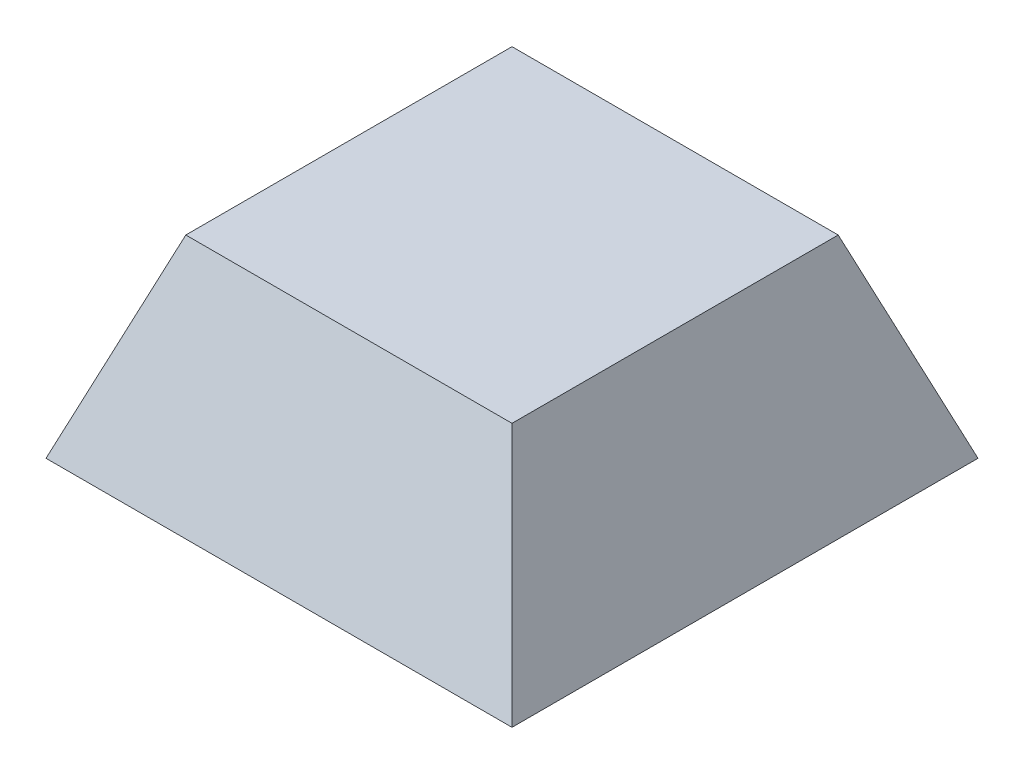
SolidWorks part; units mm, degrees
ref_plane "前视基准面" through (0, 0, 0) normal (0, 0, 1) x (1, 0, 0)
ref_plane "上视基准面" through (0, 0, 0) normal (0, 1, 0) x (1, 0, 0)
ref_plane "右视基准面" through (0, 0, 0) normal (1, 0, 0) x (0, 0, -1)
sketch "草图1" plane through (0, 0, 0) normal (0, 1, 0) x (1, 0, 0)
  line L0 (-47.5257, 0) -> (53.817, 0) construction
  line L1 (-10, 10) -> (10, 10)
  line L2 (-10, 10) -> (-10, -10)
  line L3 (-10, -10) -> (10, -10)
  line L4 (10, 10) -> (10, -10)
  line L5 (0, 37.087) -> (0, -41.1488) construction
  dimension "D1" = 20
  dimension "D2" = 20
extrude "凸台-拉伸1" add sketch "草图1" along normal blind 8.3
sketch "草图2" plane through (0, 0, 10) normal (0, 0, 1) x (1, 0, 0)
  line L0 (-10, 0) -> (-7, 8.3)
  line L1 (-10, 8.3) -> (10, 8.3) construction
  line L2 (-7, 8.3) -> (7, 8.3)
  line L3 (7, 8.3) -> (10, 0)
  line L4 (10, 0) -> (-10, 0)
  line L5 (0, -4.7277) -> (0, 9.3058) construction
  dimension "D1" = 14
extrude "切除-拉伸1" cut sketch "草图2" against normal through all flip side to cut
sketch "草图3" plane through (0, 0, 0) normal (1, 0, 0) x (0, 0, -1)
  line L0 (-10, 0) -> (10, 0)
  line L1 (-10, 0) -> (-10, 8.3) construction
  line L2 (-10, 0) -> (10, 0) construction
  line L3 (10, 0) -> (7, 8.3)
  line L4 (10, 8.3) -> (-10, 8.3) construction
  line L5 (7, 8.3) -> (-7, 8.3)
  line L6 (-7, 8.3) -> (-10, 0)
  line L7 (0, -2.62) -> (0, 10.8441) construction
  dimension "D1" = 14
extrude "切除-拉伸2" cut sketch "草图3" against normal through all and the other way through all flip side to cut
